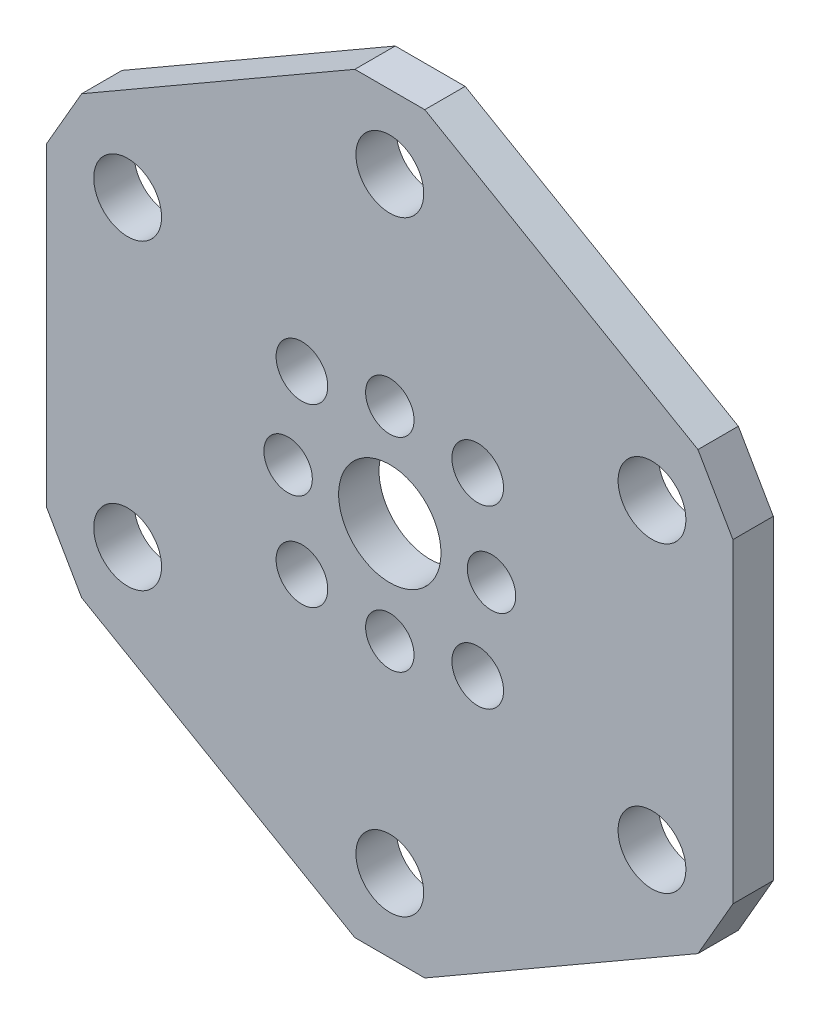
SolidWorks part; units mm, degrees
ref_plane "Front" through (0, 0, 0) normal (0, 0, 1) x (1, 0, 0)
ref_plane "Top" through (0, 0, 0) normal (0, 1, 0) x (1, 0, 0)
ref_plane "Right" through (0, 0, 0) normal (1, 0, 0) x (0, 0, -1)
ref_plane "Plane1" through (0, 0, 0) normal (0, 0, -1) x (-1, 0, 0)
sketch "Sketch1" plane through (0, 0, 0) normal (0, 0, -1) x (-1, 0, 0)
  line L0 (2.7496, 29.575) -> (-2.7496, 29.575)
  line L1 (-2.7496, 29.575) -> (-24.2379, 17.1687)
  line L2 (-24.2379, 17.1687) -> (-26.9875, 12.4062)
  line L3 (-26.9875, 12.4062) -> (-26.9875, -12.4062)
  line L4 (-26.9875, -12.4062) -> (-24.2379, -17.1687)
  line L5 (-24.2379, -17.1687) -> (-2.7496, -29.575)
  line L6 (-2.7496, -29.575) -> (2.7496, -29.575)
  line L7 (2.7496, -29.575) -> (24.2379, -17.1687)
  line L8 (24.2379, -17.1687) -> (26.9875, -12.4062)
  line L9 (26.9875, -12.4062) -> (26.9875, 12.4062)
  line L10 (26.9875, 12.4062) -> (24.2379, 17.1687)
  line L11 (24.2379, 17.1687) -> (2.7496, 29.575)
  circle A0 centre (20.6222, 11.9063) radius 2.667
  circle A1 centre (0, -23.8125) radius 2.667
  circle A2 centre (-20.6222, 11.9062) radius 2.667
  circle A3 centre (0, -8) radius 1.905
  circle A4 centre (0, 8) radius 1.905
  circle A5 centre (0, 23.8125) radius 2.667
  circle A6 centre (0, 0) radius 4.025
  circle A7 centre (-8, 0) radius 1.905
  circle A8 centre (8, 0) radius 1.905
  circle A9 centre (-20.6222, -11.9063) radius 2.667
  circle A10 centre (20.6222, -11.9063) radius 2.667
  circle A11 centre (-6.9148, 6.9148) radius 2.032
  circle A12 centre (-6.9148, -6.9148) radius 2.032
  circle A13 centre (6.9148, -6.9148) radius 2.032
  circle A14 centre (6.9148, 6.9148) radius 2.032
extrude "Boss-Extrude1" add sketch "Sketch1" against normal blind 3.175
